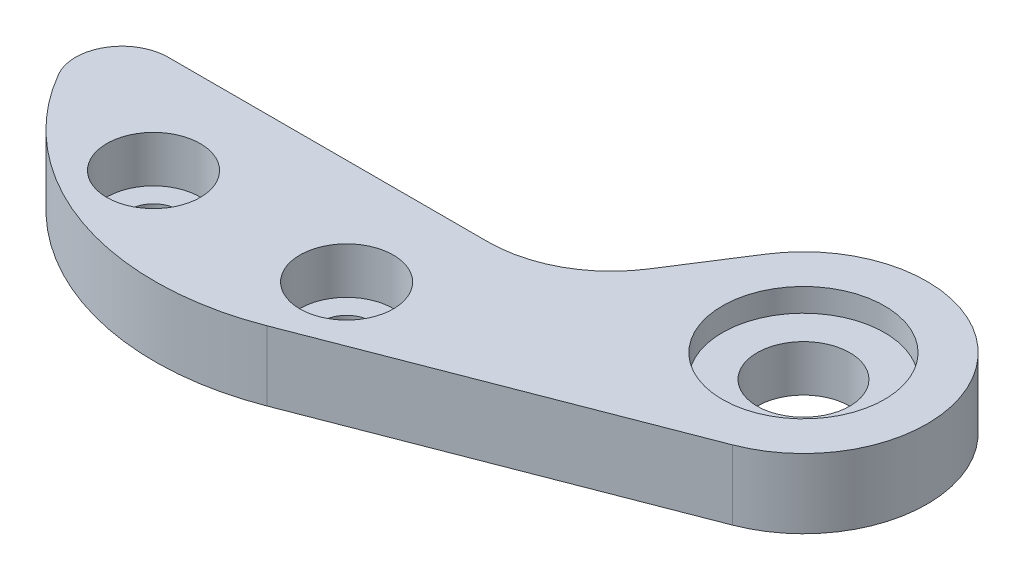
SolidWorks part; units mm, degrees
ref_plane "Спереди" through (0, 0, 0) normal (0, 0, 1) x (1, 0, 0)
ref_plane "Сверху" through (0, 0, 0) normal (0, 1, 0) x (1, 0, 0)
ref_plane "Справа" through (0, 0, 0) normal (1, 0, 0) x (0, 0, -1)
ref_plane "Плоскость4" through (0, 0, 0) normal (0, -1, 0) x (1, 0, 0)
sketch "Эскиз1" plane through (0, 0, 0) normal (0, -1, 0) x (1, 0, 0)
  line L0 (-12.1244, 4) -> (12.9364, 4)
  line L1 (12.9364, 4) -> (18.2638, -4.3156)
  line L2 (27.88, 7.4636) -> (6.12, 15.8602)
  arc A0 (6.12, 15.8602) -> (-14.7224, 8.5) centre (0, 0) ccw
  arc A1 (-14.7224, 8.5) -> (-12.1244, 4) centre (-12.1244, 7) ccw
  arc A2 (18.2638, -4.3156) -> (27.88, 7.4636) centre (25, 0) ccw
extrude "Бобышка-Вытянуть1" add sketch "Эскиз1" against normal blind 4.5
hole_wizard "Цековка для винта с заклепочной головкой M31" positions "Эскиз3" profile "Эскиз2" counterbore size "M3" standard "Ansi Metric"
sketch "Эскиз3" plane through (0, 4.5, 0) normal (0, 1, 0) x (1, 0, 0)
  point P0 (-6.25, -10.8253)
  point P1 (6.25, -10.8253)
sketch "Эскиз2" plane through (-6.25, 4.5, 10.8253) normal (1, 0, 0) x (0, 0, 1)
  line L0 (0, 0) -> (0, 4.5)
  line L1 (0, 4.5) -> (1.6, 4.5)
  line L3 (1.6, 4.5) -> (1.6, 3)
  line L4 (1.6, 3) -> (3.025, 3)
  line L5 (3.025, 3) -> (3.025, 0)
  line L7 (3.025, 0) -> (0, 0)
  line L11 (0, -6.35) -> (0, 107.95) construction
  dimension "Диаметр сквозного отверстия" = 3.2
  dimension "Глубина сквозного отверстия" = 4.5
  dimension "Диаметр цековки" = 6.05
  dimension "Глубина цековки" = 3
hole_wizard "Отверстие1" positions "Эскиз5" profile "Эскиз4" legacy
sketch "Эскиз5" plane through (0, 4.5, 0) normal (0, 1, 0) x (1, 0, 0)
  point P0 (25, 0)
sketch "Эскиз4" plane through (25, 4.5, 0) normal (1, 0, 0) x (0, 0, 1)
  line L0 (0, 0) -> (0, 4.5)
  line L1 (0, 4.5) -> (3, 4.5)
  line L2 (3, 4.5) -> (3, 1.5)
  line L3 (3, 1.5) -> (5.25, 1.5)
  line L4 (5.25, 1.5) -> (5.25, 0)
  line L5 (5.25, 0) -> (0, 0)
  line L6 (0, 110) -> (0, -10) construction
  dimension "Диаметр" = 6
  dimension "Глубина" = 4.5
  dimension "Диа. цековки" = 10.5
  dimension "Глуб. цековки" = 1.5
fillet "Скругление1" radius 8 1 edges at (12.9364, 2.25, 4)
